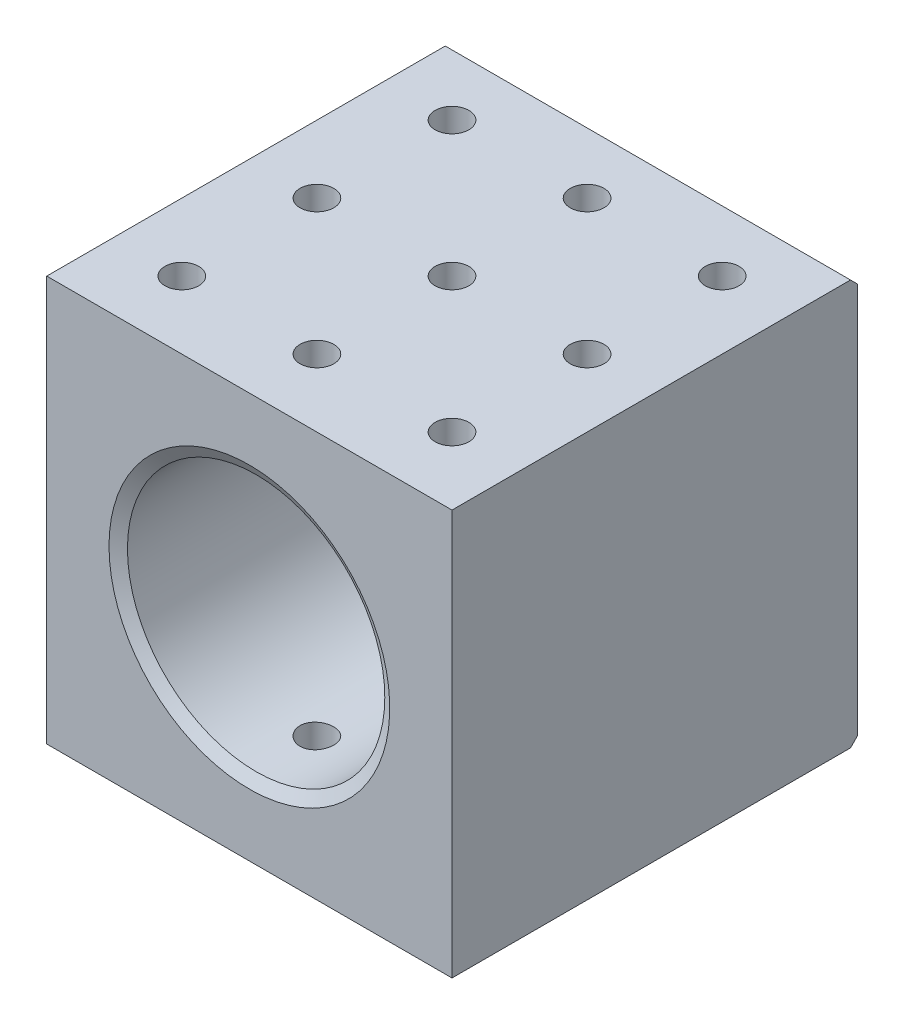
SolidWorks part; units mm, degrees
material "HDPE, Black"
ref_plane "Front Plane" through (0, 0, 0) normal (0, 0, 1) x (1, 0, 0)
ref_plane "Top Plane" through (0, 0, 0) normal (0, 1, 0) x (1, 0, 0)
ref_plane "Right Plane" through (0, 0, 0) normal (1, 0, 0) x (0, 0, -1)
sketch "Sketch1" plane through (0, 0, 0) normal (0, 0, 1) x (1, 0, 0)
  line L3 (-15, -15) -> (15, -15)
  line L4 (-15, -15) -> (-15, 15)
  line L5 (-15, 15) -> (15, 15)
  line L7 (15, 15) -> (15, -15)
  line L8 (0, 15) -> (0, -15) construction
  circle A2 centre (0, 0) radius 9.525
  point P0 (0, 0)
  dimension "D2" = 19.05
  dimension "D1" = 30
extrude "Boss-Extrude1" add sketch "Sketch1" along normal mid plane 30
chamfer "Chamfer2" distance 0.5 angle 60 2 edges at (9.525, 0, -15) (9.525, 0, 15)
chamfer "Chamfer3" distance 0.5 angle 45 2 edges at (0, -15, -15) (0, 15, -15)
mirror "Mirror1" [suppressed]
sketch "Sketch6" plane through (0, 15, 0) normal (0, 1, 0) x (1, 0, 0)
  line L0 (-10, 0) -> (10, 0) construction
  line L2 (-10, -10) -> (10, -10)
  line L3 (-10, -10) -> (-10, 10)
  line L4 (-10, 10) -> (10, 10)
  line L5 (10, -10) -> (10, 10)
  line L6 (-10, -10) -> (10, 10) construction
  line L7 (-10, 10) -> (10, -10) construction
  circle A0 centre (-10, 0) radius 1.9365
  circle A1 centre (10, 0) radius 1.9365
  point P5 (0, 0)
  dimension "D1" = 20
hole_wizard "M3x0.5 Tapped Hole1" positions "Sketch7" profile "Sketch8" tap size "M3x0.5" standard "ANSI Metric"
sketch "Sketch7" plane through (0, 15, 0) normal (0, 1, 0) x (1, 0, 0)
  line L0 (-10, 10) -> (10, 10) construction
  line L1 (-10, -10) -> (10, -10) construction
  point P0 (-10, 0)
  point P3 (10, 0)
  point P6 (0, 0)
  point P9 (-10, 10)
  point P12 (-10, -10)
  point P15 (10, 10)
  point P18 (10, -10)
  point P23 (0, 10)
  point P25 (0, -10)
sketch "Sketch8" plane through (-10, 15, 0) normal (1, 0, 0) x (0, 0, 1)
  line L0 (0, 0) -> (0, 6.7511)
  line L1 (0, 6.7511) -> (1.25, 6)
  line L2 (1.25, 6) -> (1.25, 0)
  line L5 (1.25, 0) -> (0, 0)
  line L10 (0, 6.7511) -> (-1.25, 6) construction
  line L11 (0, -6.35) -> (0, 107.95) construction
  dimension "Tap Drill Dia." = 2.5
  dimension "Tap Drill Depth" = 6
  dimension "Drill Angle" = 118
cosmetic thread "Hole Thread3" parameters "D1"=5, "D2"=3
cosmetic thread "Hole Thread4" parameters "D1"=3.0713, "D2"=3
cosmetic thread "Hole Thread9" parameters "D1"=5, "D2"=3
cosmetic thread "Hole Thread10" parameters "D1"=5, "D2"=3
cosmetic thread "Hole Thread11" parameters "D1"=5, "D2"=3
cosmetic thread "Hole Thread12" parameters "D1"=5, "D2"=3
cosmetic thread "Hole Thread13" parameters "D1"=5, "D2"=3
cosmetic thread "Hole Thread14" parameters "D1"=5, "D2"=3
cosmetic thread "Hole Thread15" parameters "D1"=5, "D2"=3
sketch "Sketch9" [suppressed] plane through (0, 0, -14.25) normal (0, 0, -1) x (-1, 0, 0)
  line L1 (0, -12) -> (-25, -12)
  line L4 (0, 0) -> (0, -12) construction
  line L5 (88, -14) -> (-88, -14) construction
  line L6 (0, -12) -> (0, -15)
  line L7 (0, -15) -> (-80, -15)
  line L8 (-80, -15) -> (-80, -14)
  arc A2 (-80, -14) -> (-78.9832, -13.963) centre (-80, 0) ccw
  arc A3 (-25, -12) -> (-78.9832, -13.963) centre (-25, -755.25) ccw
  line M13 (-88, -13.5) -> (88, -13.5)
  dimension "D1" = 50
  dimension "D3" = 12
extrude "Cut-Extrude1" [suppressed] cut sketch "Sketch9" against normal through all contours L1 A3 A2 L6 M13 | A2 L8 L7 L6 M13
mirror "Mirror2" [suppressed]
chamfer "Chamfer4" [suppressed] distance 0.5 angle 45
sketch "Sketch10" plane through (0, 0, -15) normal (0, 0, -1) x (-1, 0, 0)
  circle A0 centre (0, 0) radius 11
  dimension "D1" = 22
extrude "Cut-Extrude2" [suppressed] cut sketch "Sketch10" against normal through all
chamfer "Chamfer5" [suppressed] distance 0.254 angle 45
sketch "Sketch11" [suppressed] plane through (0, -12, 0) normal (0, -1, 0) x (1, 0, 0)
  line L0 (12.7, 0) -> (-12.7, 0) construction
  dimension "D1" = 25.4
hole_wizard "M4x0.7 Tapped Hole1" [suppressed] positions "Sketch12" profile "Sketch14" tap size "M4x0.7" standard "ANSI Metric"
sketch "Sketch12" [suppressed] plane through (0, -14, 0) normal (0, -1, 0) x (-1, 0, 0)
  point P0 (-12.7, 0)
  point P3 (12.7, 0)
sketch "Sketch14" plane through (12.7, -14, 0) normal (1, 0, 0) x (0, 0, -1)
  line L0 (0, 0) -> (0, 11.0914)
  line L1 (0, 11.0914) -> (1.65, 10.1)
  line L2 (1.65, 10.1) -> (1.65, 0)
  line L5 (1.65, 0) -> (0, 0)
  line L10 (0, 11.0914) -> (-1.65, 10.1) construction
  line L11 (0, -6.35) -> (0, 107.95) construction
  dimension "Tap Drill Dia." = 3.3
  dimension "Tap Drill Depth" = 10.1
  dimension "Drill Angle" = 118
cosmetic thread "Hole Thread5" parameters "D1"=8, "D2"=4
cosmetic thread "Hole Thread6" parameters "D1"=8, "D2"=4
sketch "Sketch15" plane through (0, -15, 0) normal (0, -1, 0) x (1, 0, 0)
  circle A0 centre (0, 0) radius 12.7 construction
  dimension "D1" = 25.4
pattern_circular "CirPattern1" count 2 over 360 about axis through (0, 0, 15) along (0, 0, -1) of "M3x0.5 Tapped Hole1"
